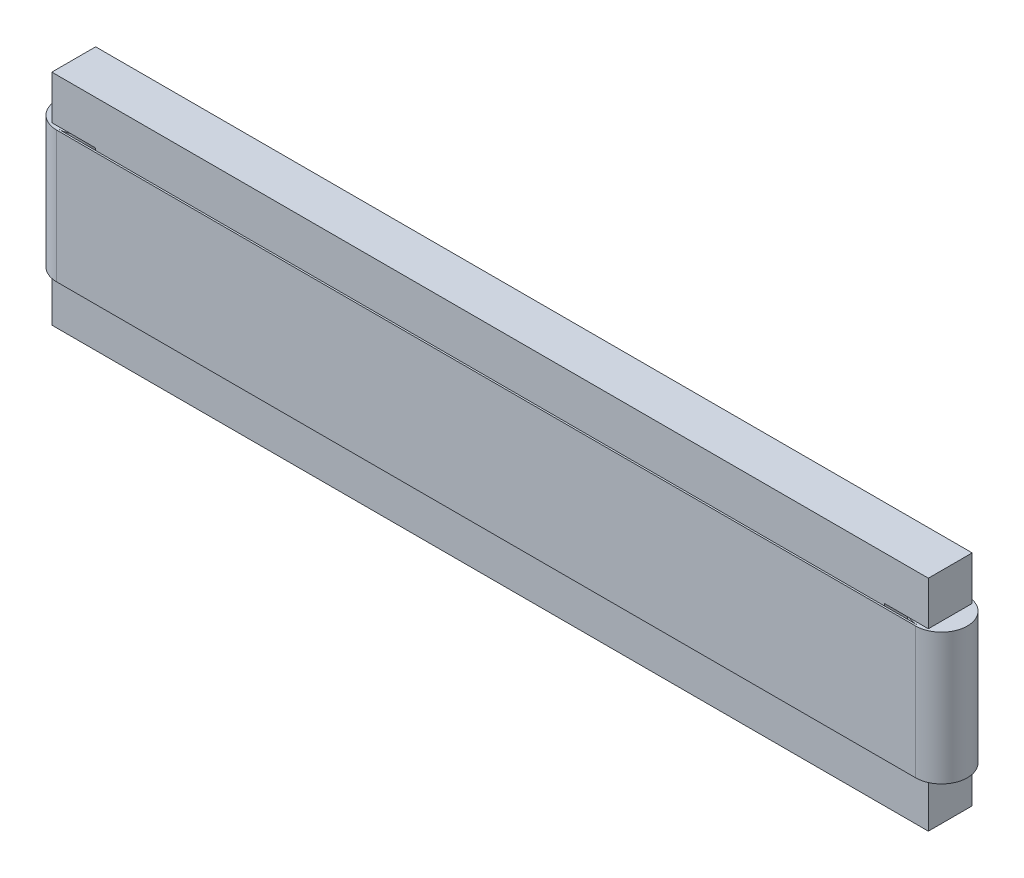
SolidWorks part; units mm, degrees
ref_plane "Front Plane" through (0, 0, 0) normal (0, 0, 1) x (1, 0, 0)
ref_plane "Top Plane" through (0, 0, 0) normal (0, 1, 0) x (1, 0, 0)
ref_plane "Right Plane" through (0, 0, 0) normal (1, 0, 0) x (0, 0, -1)
sketch "Sketch1" plane through (0, 0, 0) normal (0, 0, 1) x (1, 0, 0)
  line L5 (-500, 250) -> (500, 250)
  line L6 (500, 250) -> (500, 200)
  line L11 (500, 200) -> (450, 200)
  line L12 (450, 200) -> (450, 50)
  line L17 (450, 50) -> (500, 50)
  line L18 (500, 50) -> (500, 0)
  line L20 (500, 0) -> (-500, 0)
  line L21 (-500, 0) -> (-500, 50)
  line L22 (-500, 50) -> (-450, 50)
  line L23 (-450, 50) -> (-450, 200)
  line L25 (-500, 250) -> (-500, 200)
  line L26 (-500, 200) -> (-450, 200)
  point P0 (500, 225)
  point P6 (0, 0)
  point P15 (0, 250)
  dimension "D1" = 50
  dimension "D2" = 50
  dimension "D3" = 150
  dimension "D4" = 50
  dimension "D5" = 50
  dimension "D6" = 50
  dimension "D7" = 50
  dimension "D8" = 1000
  dimension "D9" = 1000
extrude "Boss-Extrude2" add sketch "Sketch1" along normal blind 50
sketch "Sketch2" plane through (0, 200, 0) normal (0, -1, 0) x (1, 0, 0)
  line L0 (-500, 25) -> (-172.8492, 25) construction
  line L1 (-500, 50) -> (-500, 0) construction
  circle A0 centre (-490, 25) radius 27.5
  dimension "D1" = 55
  dimension "D2" = 10
extrude "Boss-Extrude3" add sketch "Sketch2" along normal blind 150
mirror "Mirror1" about plane through (0, 0, 0) normal (1, 0, 0) of "Boss-Extrude3"
sketch "Sketch3" plane through (0, 50, 0) normal (0, -1, 0) x (1, 0, 0)
  line L0 (-490, 52.5) -> (490, 52.5)
  line L2 (490, -2.5) -> (-490, -2.5)
  line L3 (-490, 54.5) -> (490, 54.5)
  line L4 (490, -4.5) -> (-490, -4.5)
  arc A0 (-490, 52.5) -> (-490, -2.5) centre (-490, 25) ccw
  arc A1 (490, -2.5) -> (490, 52.5) centre (490, 25) ccw
  arc A2 (490, -4.5) -> (490, 54.5) centre (490, 25) ccw
  arc A3 (-490, 54.5) -> (-490, -4.5) centre (-490, 25) ccw
  dimension "D1" = 2
extrude "Boss-Extrude4" add sketch "Sketch3" against normal blind 150
